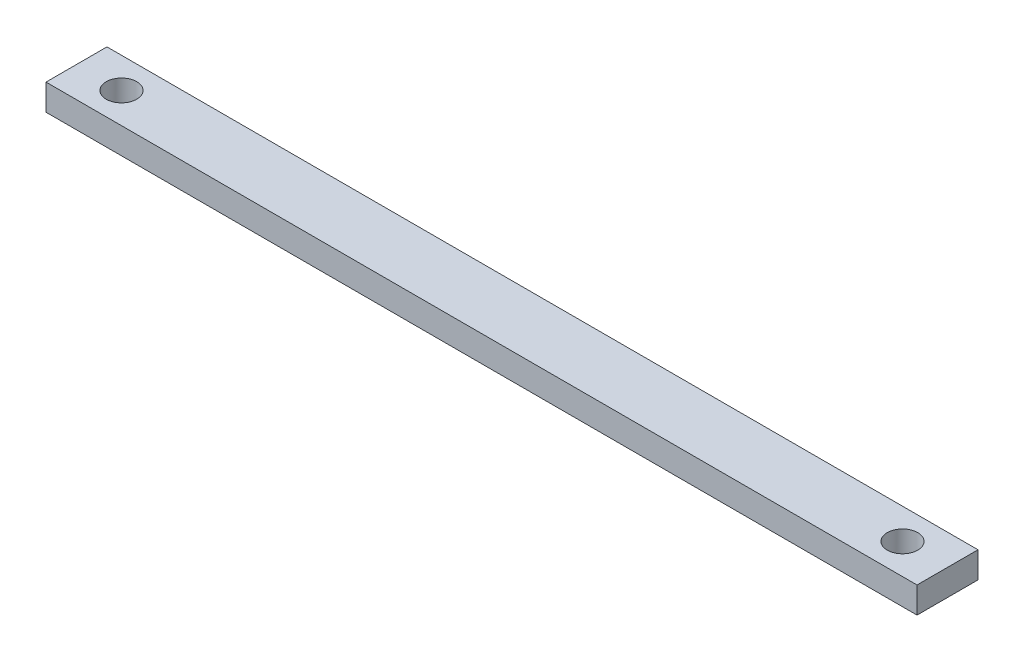
SolidWorks part; units mm, degrees
ref_plane "Plan de face" through (0, 0, 0) normal (0, 0, 1) x (1, 0, 0)
ref_plane "Plan de dessus" through (0, 0, 0) normal (0, 1, 0) x (1, 0, 0)
ref_plane "Plan de droite" through (0, 0, 0) normal (1, 0, 0) x (0, 0, -1)
sketch "Esquisse1" plane through (0, 0, 0) normal (0, 1, 0) x (1, 0, 0)
  line L1 (-300, -21) -> (300, -21)
  line L2 (-300, -21) -> (-300, 21)
  line L3 (-300, 21) -> (300, 21)
  line L4 (300, -21) -> (300, 21)
  line L5 (-300, -21) -> (300, 21) construction
  line L6 (-300, 21) -> (300, -21) construction
  point P0 (0, 0)
  dimension "D1" = 600
  dimension "D2" = 42
extrude "Boss.-Extru.1" add sketch "Esquisse1" along normal blind 18
sketch "Esquisse2" plane through (0, 18, 0) normal (0, 1, 0) x (1, 0, 0)
  line L0 (-238, 21) -> (-238, -21) construction
  line L2 (300, 21) -> (-300, 21) construction
  line L4 (-300, -21) -> (300, -21) construction
  line L5 (-238, 0) -> (-300, 0) construction
  line L6 (-300, 21) -> (-300, -21) construction
  line L8 (238, 21) -> (238, -21) construction
  line L9 (238, 0) -> (300, 0) construction
  line L10 (300, -21) -> (300, 21) construction
  circle A2 centre (269, 0) radius 10.5
  circle A3 centre (-269, 0) radius 10.5
  dimension "D1" = 62
  dimension "D2" = 21
  dimension "D4" = 21
  dimension "D3" = 62
extrude "Enlèv. mat.-Extru.1" cut sketch "Esquisse2" against normal blind 20
